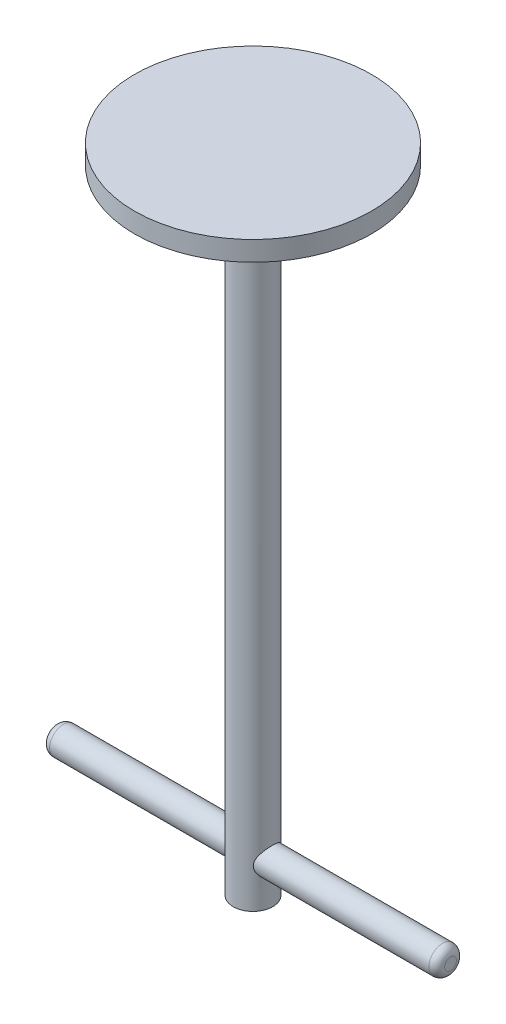
SolidWorks part; units mm, degrees
material "6061 Alloy"
ref_plane "Front Plane" through (0, 0, 0) normal (0, 0, 1) x (1, 0, 0)
ref_plane "Top Plane" through (0, 0, 0) normal (0, 1, 0) x (1, 0, 0)
ref_plane "Right Plane" through (0, 0, 0) normal (1, 0, 0) x (0, 0, -1)
sketch "Sketch1" plane through (0, 0, 0) normal (0, 1, 0) x (1, 0, 0)
  circle A0 centre (0, 0) radius 6.35
  dimension "D1" = 12.7
extrude "Boss-Extrude1" add sketch "Sketch1" along normal blind 203.2
chamfer "Chamfer1" distance 2.54 angle 45 1 edges at (0, 203.2, 6.35)
sketch "Sketch3" plane through (0, 203.2, 0) normal (0, 1, 0) x (1, 0, 0)
  circle A0 centre (0, 0) radius 38.1
  dimension "D1" = 76.2
extrude "Boss-Extrude2" add sketch "Sketch3" along normal blind 6.35
sketch "Sketch4" plane through (0, 0, 0) normal (1, 0, 0) x (0, 0, -1)
  line L0 (0, 0) -> (0, 12.7) construction
  circle A0 centre (0, 12.7) radius 4.445
  dimension "D2" = 8.89
  dimension "D1" = 12.7
extrude "Boss-Extrude3" add sketch "Sketch4" along normal mid plane 127
fillet "Fillet2" radius 2.54 2 edges at (63.5, 12.7, -4.445) (-63.5, 12.7, -4.445)
